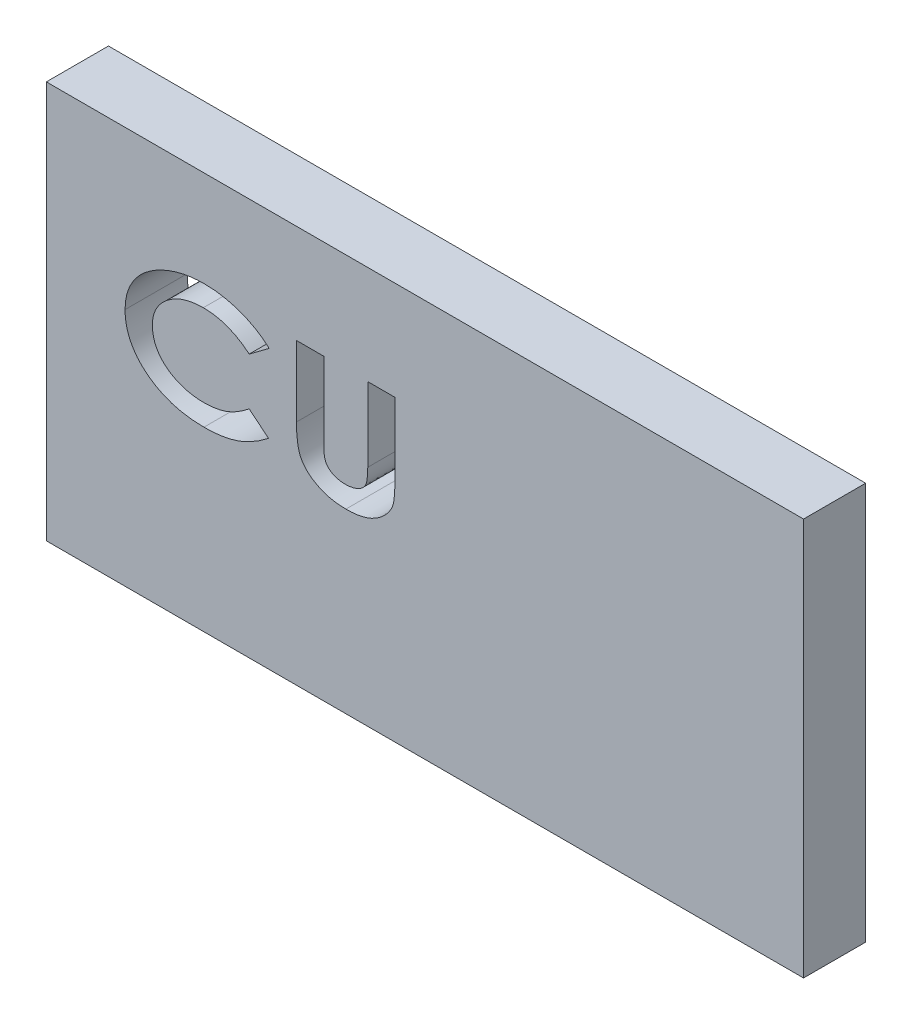
SolidWorks part; units mm, degrees
material "PBT General Purpose"
ref_plane "Front Plane" through (0, 0, 0) normal (0, 0, 1) x (1, 0, 0)
ref_plane "Top Plane" through (0, 0, 0) normal (0, 1, 0) x (1, 0, 0)
ref_plane "Right Plane" through (0, 0, 0) normal (1, 0, 0) x (0, 0, -1)
sketch "Sketch1" plane through (0, 0, 0) normal (0, 0, 1) x (1, 0, 0)
  line L0 (0, 0) -> (0, 32)
  line L1 (0, 32) -> (60.96, 32)
  line L2 (60.96, 32) -> (60.96, 0)
  line L3 (60.96, 0) -> (0, 0)
  dimension "D1" = 32
  dimension "D2" = 60.96
extrude "Boss-Extrude1" add sketch "Sketch1" along normal blind 5 contours L0 L1 L2 L3
sketch "Sketch2" plane through (0, 0, 5) normal (0, 0, 1) x (1, 0, 0)
  text T0 "CU" font "Century Gothic" height in points 36
extrude "Emboss ID" cut sketch "Sketch2" against normal through all
